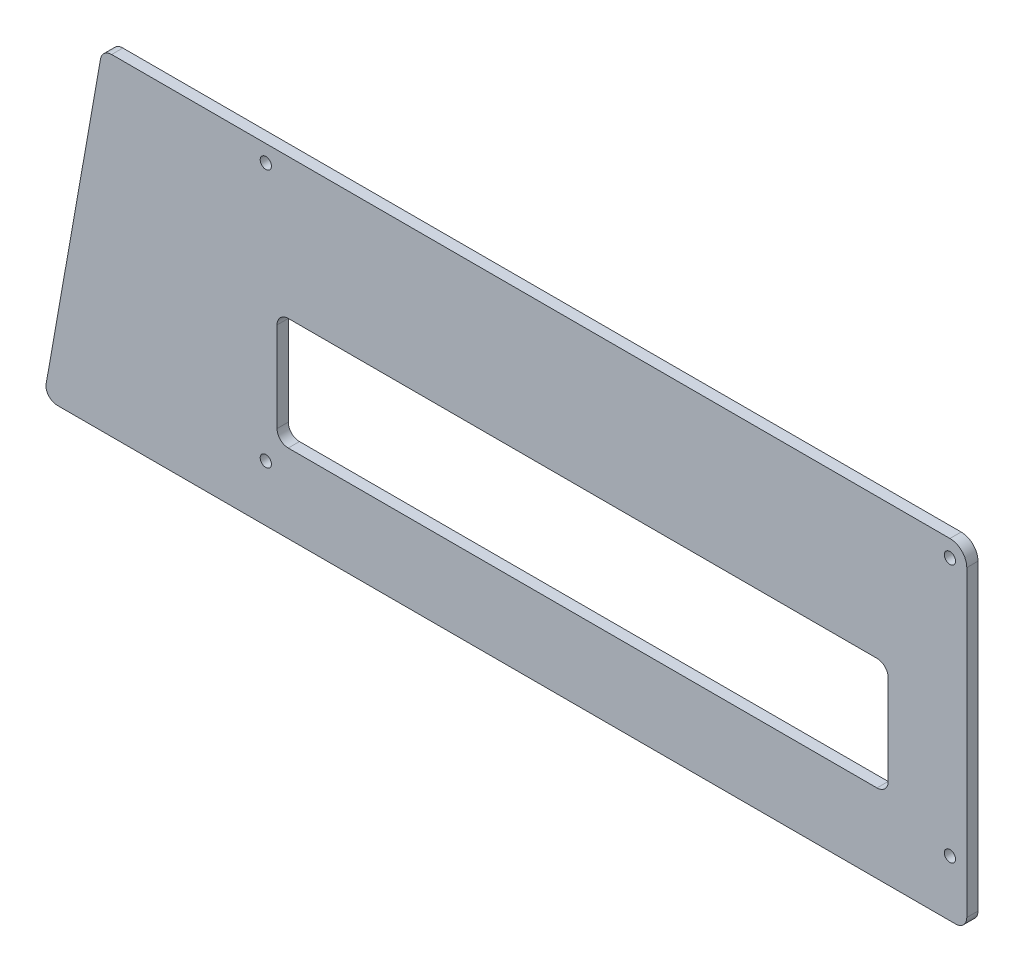
SolidWorks part; units mm, degrees
ref_plane "Front Plane" through (0, 0, 0) normal (0, 0, 1) x (1, 0, 0)
ref_plane "Top Plane" through (0, 0, 0) normal (0, 1, 0) x (1, 0, 0)
ref_plane "Right Plane" through (0, 0, 0) normal (1, 0, 0) x (0, 0, -1)
sketch "Sketch1" plane through (0, 0, 0) normal (0, 0, 1) x (1, 0, 0)
  line L0 (68.1647, -23.6199) -> (-749.2353, -23.6199) construction
  line L1 (68.1647, -23.6199) -> (68.1647, 436.3801)
  line L2 (48.1647, -23.6199) -> (48.1647, 436.3801)
  line L3 (-541.4353, -23.6199) -> (-541.4353, 436.3801)
  line L4 (-561.4353, -23.6199) -> (-561.4353, 436.3801)
  line L5 (-739.2353, -23.6199) -> (-739.2353, 436.3801)
  line L6 (-749.2353, -23.6199) -> (-749.2353, 436.3801)
  line L7 (68.1647, -23.6199) -> (68.1647, 199.2967) construction
  line L8 (68.1647, 436.3801) -> (-749.2353, 436.3801) construction
  line L9 (68.1647, -23.6199) -> (-749.2353, -23.6199) construction
  line L10 (-326.0325, 436.3801) -> (-346.4221, 436.3801) construction
  line L11 (-749.2353, -23.6199) -> (-749.2353, 214.2505) construction
  line L12 (-326.0325, 436.3801) -> (-326.0325, 436.3801) construction
  line L13 (-346.4221, 436.3801) -> (-346.4221, 436.3801) construction
  line L14 (-551.4353, -23.6199) -> (-551.4353, 436.3801) construction
  line L16 (58.1647, -23.6199) -> (58.1647, 436.3801) construction
sketch "Sketch2" plane through (0, 0, 0) normal (0, 0, 1) x (1, 0, 0)
  line L0 (-737.3178, -23.6199) -> (63.1647, -23.6199)
  line L1 (-531.4353, 46.3801) -> (-6.8353, 46.3801)
  line L2 (73.1647, 256.3801) -> (73.1647, -13.6199)
  line L3 (58.1647, 271.3801) -> (-688.8278, 271.3801)
  line L4 (-747.1658, -11.8834) -> (-698.6759, 263.1166)
  line L5 (3.1647, 136.3801) -> (3.1647, 56.3801)
  line L6 (-441.4353, 146.3801) -> (-96.8353, 146.3801) construction
  line L7 (-541.4353, 56.3801) -> (-541.4353, 136.3801)
  line L8 (-665.8125, 46.3801) -> (-638.4819, 201.3801) construction
  line L10 (3.1647, 201.3801) -> (-638.4819, 201.3801) construction
  line L11 (-665.8125, 46.3801) -> (3.1647, 46.3801) construction
  line L12 (3.1647, 201.3801) -> (3.1647, 46.3801) construction
  line L13 (-531.4353, 146.3801) -> (-6.8353, 146.3801)
  line L14 (-541.4353, 56.3801) -> (-541.4353, 191.3801) construction
  line L15 (-441.4353, 146.3801) -> (-441.4353, 191.3801) construction
  line L16 (-96.8353, 191.3801) -> (-96.8353, 146.3801) construction
  line L17 (3.1647, 191.3801) -> (3.1647, 56.3801) construction
  circle A0 centre (58.1647, 256.3801) radius 5
  circle A1 centre (-551.4353, 26.3801) radius 5
  circle A2 centre (58.1647, 26.3801) radius 5
  circle A3 centre (-551.4353, 256.3801) radius 5
  circle A4 centre (58.1647, 256.3801) radius 15 construction
  circle A5 centre (-551.4353, 256.3801) radius 15 construction
  arc A6 (58.1647, 271.3801) -> (73.1647, 256.3801) centre (58.1647, 256.3801) cw
  arc A7 (63.1647, -23.6199) -> (73.1647, -13.6199) centre (63.1647, -13.6199) ccw
  arc A8 (-737.3178, -23.6199) -> (-747.1658, -11.8834) centre (-737.3178, -13.6199) cw
  arc A9 (-688.8278, 271.3801) -> (-698.6759, 263.1166) centre (-688.8278, 261.3801) ccw
  arc A10 (3.1647, 136.3801) -> (-6.8353, 146.3801) centre (-6.8353, 136.3801) ccw
  arc A11 (-6.8353, 46.3801) -> (3.1647, 56.3801) centre (-6.8353, 56.3801) ccw
  arc A12 (-541.4353, 56.3801) -> (-531.4353, 46.3801) centre (-531.4353, 56.3801) ccw
  arc A14 (-638.4819, 201.3801) -> (-638.4819, 201.3801) centre (-638.4819, 201.3801) ccw construction
  arc A15 (-665.8125, 46.3801) -> (-665.8125, 46.3801) centre (-665.8125, 46.3801) cw construction
  arc A16 (3.1647, 201.3801) -> (3.1647, 201.3801) centre (3.1647, 201.3801) cw construction
  arc A17 (3.1647, 46.3801) -> (3.1647, 46.3801) centre (3.1647, 46.3801) ccw construction
  arc A18 (-531.4353, 146.3801) -> (-541.4353, 136.3801) centre (-531.4353, 136.3801) ccw
  arc A19 (-441.4353, 146.3801) -> (-441.4353, 146.3801) centre (-441.4353, 146.3801) ccw construction
  arc A20 (-96.8353, 146.3801) -> (-96.8353, 146.3801) centre (-96.8353, 146.3801) ccw construction
  point P28 (-749.2353, -23.6199)
  dimension "D1" = 50
  dimension "D3" = 10
  dimension "D4" = 10
  dimension "D5" = 10
  dimension "D6" = 10
  dimension "D7" = 10
  dimension "D2" = 280
sketch "Sketch3" plane through (0, 0, 0) normal (0, 0, 1) x (1, 0, 0)
  line L1 (-531.4353, 71.3801) -> (-442.5353, 71.3801)
  line L2 (-531.4353, 71.3801) -> (-531.4353, 56.3801)
  line L3 (-531.4353, 56.3801) -> (-442.5353, 56.3801)
  line L4 (-442.5353, 71.3801) -> (-442.5353, 56.3801)
extrude "Boss-Extrude1" add sketch "Sketch2" along normal blind 10
sketch "Sketch4" plane through (0, 0, 0) normal (0, 0, 1) x (1, 0, 0)
  line L0 (-532.9779, 100.6337) -> (-532.9779, 94.2837)
  line L1 (-508.9779, 118.6087) -> (-461.4779, 118.6087)
  line L2 (-508.9779, 118.6087) -> (-508.9779, 100.6337)
  line L3 (-508.9779, 76.3087) -> (-461.4779, 76.3087)
  line L4 (-461.4779, 118.6087) -> (-461.4779, 100.6337)
  line L5 (-508.9779, 100.6337) -> (-532.9779, 100.6337)
  line L6 (-508.9779, 94.2837) -> (-532.9779, 94.2837)
  line L7 (-451.4779, 100.6337) -> (-451.4779, 94.2837)
  line L8 (-461.4779, 100.6337) -> (-451.4779, 100.6337)
  line L9 (-461.4779, 94.2837) -> (-451.4779, 94.2837)
  line L10 (-461.4779, 94.2837) -> (-461.4779, 76.3087)
  line L11 (-508.9779, 94.2837) -> (-508.9779, 76.3087)
  dimension "D1" = 47.5
  dimension "D2" = 42.3
sketch "NEMA17_positions" plane through (0, 0, 0) normal (0, 0, 1) x (1, 0, 0)
  line L0 (-482.3506, 54.4332) -> (-488.7006, 54.4332)
  line L1 (-464.3756, 30.4332) -> (-464.3756, -17.0668)
  line L2 (-464.3756, 30.4332) -> (-482.3506, 30.4332)
  line L3 (-506.6756, 30.4332) -> (-506.6756, -17.0668)
  line L4 (-464.3756, -17.0668) -> (-482.3506, -17.0668)
  line L5 (-482.3506, 30.4332) -> (-482.3506, 54.4332)
  line L6 (-488.7006, 30.4332) -> (-488.7006, 54.4332)
  line L7 (-482.3506, -27.0668) -> (-488.7006, -27.0668)
  line L8 (-482.3506, -17.0668) -> (-482.3506, -27.0668)
  line L9 (-488.7006, -17.0668) -> (-488.7006, -27.0668)
  line L10 (-488.7006, -17.0668) -> (-506.6756, -17.0668)
  line L11 (-488.7006, 30.4332) -> (-506.6756, 30.4332)
  dimension "D1" = 47.5
  dimension "D2" = 42.3
sketch "Sketch5" plane through (0, 0, 0) normal (0, 0, 1) x (1, 0, 0)
  line L0 (-404.862, 32.5293) -> (-425.436, 32.5293)
  line L1 (-466.584, 57.9293) -> (-425.436, 57.9293)
  line L2 (-466.584, 57.9293) -> (-466.584, 0.7793)
  line L3 (-466.584, 0.7793) -> (-425.436, 0.7793)
  line L4 (-425.436, 57.9293) -> (-425.436, 32.5293)
  line L5 (-404.862, 26.1793) -> (-425.436, 26.1793)
  line L6 (-425.436, 26.1793) -> (-425.436, 0.7793)
  line L7 (-404.862, 32.5293) -> (-404.862, 26.1793)
  line L8 (-404.862, 26.1793) -> (-404.8476, 26.1484)
  dimension "D1" = 57.15
  dimension "D2" = 41.148
